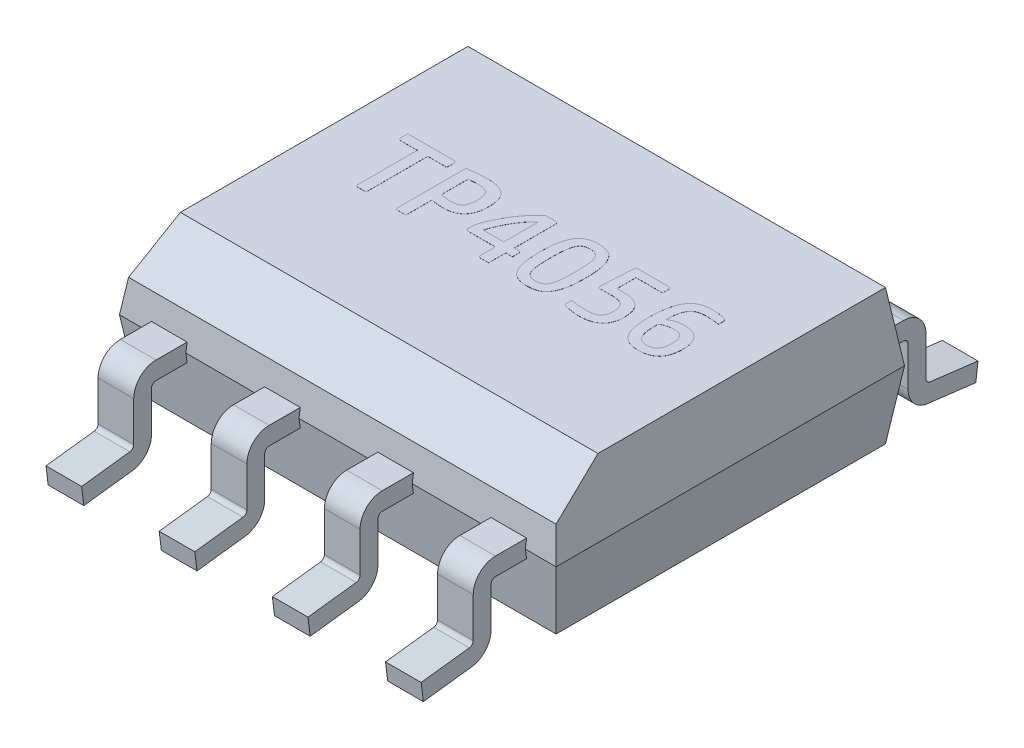
SolidWorks part; units mm, degrees
ref_plane "Front" through (0, 0, 0) normal (0, 0, 1) x (1, 0, 0)
ref_plane "Top" through (0, 0, 0) normal (0, 1, 0) x (1, 0, 0)
ref_plane "Right" through (0, 0, 0) normal (1, 0, 0) x (0, 0, -1)
sketch "Sketch1" plane through (0, 0, 0) normal (0, 1, 0) x (1, 0, 0)
  line L1 (-2.45, -1.955) -> (2.45, -1.955)
  line L2 (-2.45, -1.955) -> (-2.45, 1.955)
  line L3 (-2.45, 1.955) -> (2.45, 1.955)
  line L4 (2.45, -1.955) -> (2.45, 1.955)
  line L5 (-2.45, -1.955) -> (2.45, 1.955) construction
  line L6 (-2.45, 1.955) -> (2.45, -1.955) construction
  point P0 (0, 0)
  dimension "D1" = 4.9
  dimension "D2" = 3.91
extrude "Extrude1" add sketch "Sketch1" along normal mid plane 1.52 draft 8
chamfer "Chamfer1" distance 0.4 angle 45 1 edges at (0, 0.76, 1.8482)
ref_plane "Plane1" through (1.905, 0, 0) normal (1, 0, 0) x (0, 0, -1)
sketch "Sketch5" plane through (1.905, 0, 0) normal (1, 0, 0) x (0, 0, -1)
  line L0 (0, 0.1) -> (-2.29, 0.1)
  line L1 (-2.54, -0.15) -> (-2.54, -0.5955)
  line L2 (-2.5839, -0.6451) -> (-3.1244, -0.7115)
  line L3 (0, -0.1) -> (-2.29, -0.1)
  line L4 (0, 0.1) -> (0, -0.1) construction
  line L5 (-3.1244, -0.7115) -> (-3.1, -0.91)
  line L6 (-2.34, -0.15) -> (-2.34, -0.5955)
  line L7 (-2.5595, -0.8436) -> (-3.1, -0.91)
  line L9 (2.2739, 0) -> (-2.2739, 0) construction
  line L11 (-1.8482, -0.76) -> (1.8482, -0.76) construction
  line L12 (0, 1.2508) -> (0, -1.2508) construction
  line L13 (2.5595, -0.8436) -> (3.1, -0.91)
  line L14 (2.34, -0.15) -> (2.34, -0.5955)
  line L15 (3.1244, -0.7115) -> (3.1, -0.91)
  line L16 (0, -0.1) -> (2.29, -0.1)
  line L17 (2.5839, -0.6451) -> (3.1244, -0.7115)
  line L18 (2.54, -0.15) -> (2.54, -0.5955)
  line L19 (0, 0.1) -> (2.29, 0.1)
  arc A0 (-2.54, -0.5955) -> (-2.5839, -0.6451) centre (-2.59, -0.5955) cw
  arc A1 (-2.29, 0.1) -> (-2.54, -0.15) centre (-2.29, -0.15) ccw
  arc A2 (-2.29, -0.1) -> (-2.34, -0.15) centre (-2.29, -0.15) ccw
  arc A3 (-2.34, -0.5955) -> (-2.5595, -0.8436) centre (-2.59, -0.5955) cw
  arc A4 (2.34, -0.5955) -> (2.5595, -0.8436) centre (2.59, -0.5955) ccw
  arc A5 (2.29, -0.1) -> (2.34, -0.15) centre (2.29, -0.15) cw
  arc A6 (2.29, 0.1) -> (2.54, -0.15) centre (2.29, -0.15) cw
  arc A7 (2.54, -0.5955) -> (2.5839, -0.6451) centre (2.59, -0.5955) ccw
  arc A8 (-2.29, 0.1) -> (-2.54, -0.15) centre (-2.29, -0.15) ccw construction
  arc A9 (-2.54, -0.5955) -> (-2.5839, -0.6451) centre (-2.59, -0.5955) cw construction
  point P13 (-2.3, -0.4503)
  dimension "D6" = 0.15
  dimension "D7" = 0.76
  dimension "D5" = 0.25
  dimension "D1" = 0.2
  dimension "D2" = 0.1
  dimension "D3" = 7
  dimension "D4" = 6.2
extrude "Extrude3" add sketch "Sketch5" along normal mid plane 0.4
pattern_linear "LPattern3" count 4 spacing 1.27 along (-1, 0, 0) of "Extrude3"
sketch "Sketch6" plane through (0, 0.76, 0) normal (0, 1, 0) x (1, 0, 0)
  line L0 (-2.3432, -0.1396) -> (2.3432, -0.1396) construction
  line L1 (-2.3432, 1.8482) -> (-2.3432, -1.3782) construction
  line L2 (2.3432, -1.3782) -> (2.3432, 1.8482) construction
  text T0 "TP4056" font "@Adobe Fan Heiti Std B" height 0.8
extrude "Boss-Extrude1" add sketch "Sketch6" along normal blind 0.001
